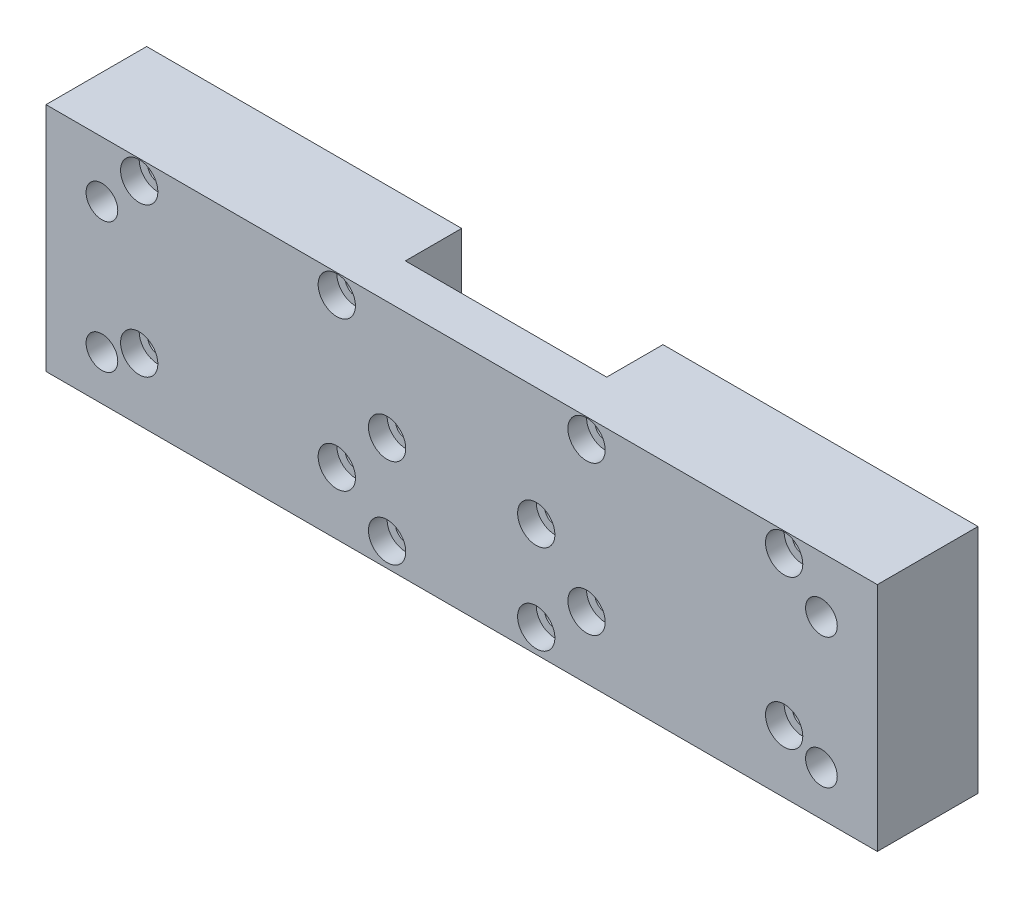
SolidWorks part; units mm, degrees
ref_plane "Front Plane" through (0, 0, 0) normal (0, 0, 1) x (1, 0, 0)
ref_plane "Top Plane" through (0, 0, 0) normal (0, 1, 0) x (1, 0, 0)
ref_plane "Right Plane" through (0, 0, 0) normal (1, 0, 0) x (0, 0, -1)
sketch "Sketch1" plane through (0, 0, 0) normal (0, 1, 0) x (1, 0, 0)
  line L0 (-27, 0) -> (27, 0)
  line L1 (27, 0) -> (27, 15.1)
  line L2 (27, 15.1) -> (111.5, 15.1)
  line L3 (111.5, 15.1) -> (111.5, -11.9)
  line L4 (111.5, -11.9) -> (-111.5, -11.9)
  line L5 (0, 0) -> (0, 64.75) construction
  line L6 (-111.5, 15.1) -> (-111.5, -11.9)
  line L7 (-27, 15.1) -> (-111.5, 15.1)
  line L8 (-27, 0) -> (-27, 15.1)
  point P9 (0, -11.9)
  dimension "D1" = 54
  dimension "D2" = 223
  dimension "D3" = 15.1
  dimension "D4" = 27
extrude "Boss-Extrude1" add sketch "Sketch1" along normal mid plane 62
sketch "Sketch2" plane through (0, 0, 11.9) normal (0, 0, 1) x (1, 0, 0)
  line L0 (0, -1.5) -> (0, 0) construction
  line L5 (-96.5, -19) -> (96.5, -19) construction
  line L6 (-96.5, -19) -> (-96.5, 16) construction
  line L7 (-96.5, 16) -> (96.5, 16) construction
  line L8 (96.5, -19) -> (96.5, 16) construction
  line L9 (-96.5, -19) -> (96.5, 16) construction
  line L10 (-96.5, 16) -> (96.5, -19) construction
  line L11 (-111.5, 31) -> (111.5, 31) construction
  point P0 (0, -1.5)
  point P6 (0, -3.7594)
  dimension "D1" = 193
  dimension "D2" = 35
  dimension "D3" = 15
hole_wizard "M10x1.5 Tapped Hole1" positions "Sketch3" profile "Sketch4" tap size "M10x1.5" standard "ANSI Metric" end condition through all
sketch "Sketch3" plane through (0, 0, 11.9) normal (0, 0, 1) x (1, 0, 0)
  point P0 (-96.5, 16)
  point P3 (-96.5, -19)
  point P6 (96.5, 16)
  point P9 (96.5, -19)
sketch "Sketch4" plane through (-96.5, 16, 11.9) normal (1, 0, 0) x (0, -1, 0)
  line L0 (0, 0) -> (0, 27)
  line L1 (0, 27) -> (4.25, 27)
  line L2 (4.25, 27) -> (4.25, 0)
  line L5 (4.25, 0) -> (0, 0)
  line L11 (0, -6.35) -> (0, 107.95) construction
  dimension "Thru Tap Drill Dia." = 8.5
  dimension "Thru Tap Drill Depth" = 27
cosmetic thread "Hole Thread1" parameters "D2"=10
cosmetic thread "Hole Thread2" parameters "D2"=10
cosmetic thread "Hole Thread3" parameters "D2"=10
cosmetic thread "Hole Thread4" parameters "D2"=10
sketch "Sketch5" plane through (0, 0, 11.9) normal (0, 0, 1) x (1, 0, 0)
  line L0 (-111.5, 31) -> (111.5, 31) construction
  line L1 (-86.5, -14.25) -> (-33.5, -14.25) construction
  line L2 (-86.5, -14.25) -> (-86.5, 25.75) construction
  line L3 (-86.5, 25.75) -> (-33.5, 25.75) construction
  line L4 (-33.5, -14.25) -> (-33.5, 25.75) construction
  line L5 (-86.5, -14.25) -> (-33.5, 25.75) construction
  line L6 (-86.5, 25.75) -> (-33.5, -14.25) construction
  line L7 (-111.5, 31) -> (-111.5, -31) construction
  line L8 (0, 0) -> (0, 64.4282) construction
  line L9 (86.5, 25.75) -> (33.5, -14.25) construction
  line L10 (86.5, -14.25) -> (33.5, 25.75) construction
  line L11 (33.5, -14.25) -> (33.5, 25.75) construction
  line L12 (86.5, 25.75) -> (33.5, 25.75) construction
  line L13 (86.5, -14.25) -> (86.5, 25.75) construction
  line L14 (86.5, -14.25) -> (33.5, -14.25) construction
  point P0 (-60, 5.75)
  point P16 (60, 5.75)
  dimension "D1" = 53
  dimension "D2" = 40
  dimension "D3" = 5.25
  dimension "D4" = 25
hole_wizard "CBORE for M5 SHCS1" positions "Sketch6" profile "Sketch7" counterbore size "M5" standard "ANSI Metric" end condition through all
sketch "Sketch6" plane through (0, 0, 11.9) normal (0, 0, 1) x (1, 0, 0)
  point P0 (-86.5, 25.75)
  point P3 (-86.5, -14.25)
  point P6 (-33.5, 25.75)
  point P9 (-33.5, -14.25)
  point P12 (33.5, 25.75)
  point P15 (86.5, 25.75)
  point P18 (33.5, -14.25)
  point P21 (86.5, -14.25)
sketch "Sketch7" plane through (-86.5, 25.75, 11.9) normal (1, 0, 0) x (0, -1, 0)
  line L0 (0, 0) -> (0, 27)
  line L1 (0, 27) -> (2.75, 27)
  line L3 (2.75, 27) -> (2.75, 5)
  line L4 (2.75, 5) -> (5, 5)
  line L5 (5, 5) -> (5, 0)
  line L7 (5, 0) -> (0, 0)
  line L11 (0, -6.35) -> (0, 107.95) construction
  dimension "Thru Hole Dia." = 5.5
  dimension "Thru Hole Depth" = 27
  dimension "C'Bore Dia." = 10
  dimension "C'Bore Depth" = 5
sketch "Sketch8" plane through (0, 0, 11.9) normal (0, 0, 1) x (1, 0, 0)
  line L0 (0, -12.65) -> (0, 0) construction
  line L1 (-20, -24.65) -> (20, -24.65) construction
  line L2 (-20, -24.65) -> (-20, -0.65) construction
  line L3 (-20, -0.65) -> (20, -0.65) construction
  line L4 (20, -24.65) -> (20, -0.65) construction
  line L5 (-20, -24.65) -> (20, -0.65) construction
  line L6 (-20, -0.65) -> (20, -24.65) construction
  line L7 (-111.5, -31) -> (111.5, -31) construction
  point P0 (0, -12.65)
  dimension "D1" = 40
  dimension "D2" = 24
  dimension "D3" = 6.35
hole_wizard "CBORE for M5 SHCS2" positions "Sketch9" profile "Sketch10" counterbore size "M5" standard "ANSI Metric" end condition through all
sketch "Sketch9" plane through (0, 0, 11.9) normal (0, 0, 1) x (1, 0, 0)
  point P0 (-20, -0.65)
  point P3 (20, -0.65)
  point P6 (20, -24.65)
  point P9 (-20, -24.65)
sketch "Sketch10" plane through (-20, -0.65, 11.9) normal (1, 0, 0) x (0, -1, 0)
  line L0 (0, 0) -> (0, 27)
  line L1 (0, 27) -> (2.75, 27)
  line L3 (2.75, 27) -> (2.75, 5)
  line L4 (2.75, 5) -> (5, 5)
  line L5 (5, 5) -> (5, 0)
  line L7 (5, 0) -> (0, 0)
  line L11 (0, -6.35) -> (0, 107.95) construction
  dimension "Thru Hole Dia." = 5.5
  dimension "Thru Hole Depth" = 27
  dimension "C'Bore Dia." = 10
  dimension "C'Bore Depth" = 5
